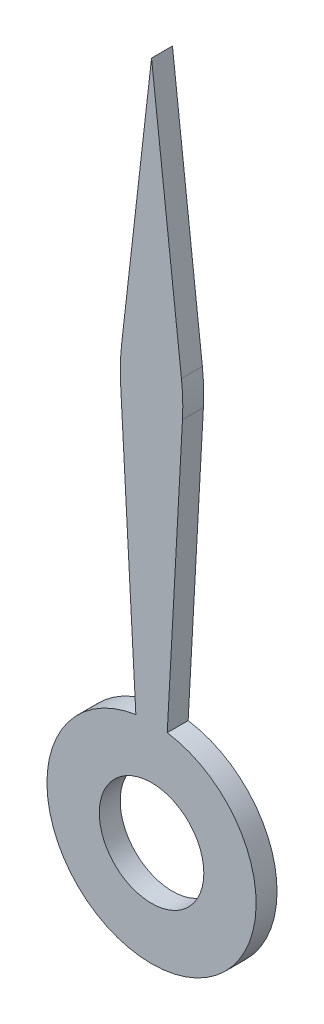
SolidWorks part; units mm, degrees
ref_plane "Front Plane" through (0, 0, 0) normal (0, 0, 1) x (1, 0, 0)
ref_plane "Top Plane" through (0, 0, 0) normal (0, 1, 0) x (1, 0, 0)
ref_plane "Right Plane" through (0, 0, 0) normal (1, 0, 0) x (0, 0, -1)
sketch "Sketch1" plane through (0, 0, 0) normal (0, 0, 1) x (1, 0, 0)
  line L0 (0, 0) -> (0, 6.5) construction
  line L1 (0, 6.5) -> (-0.286, 3.9895)
  line L2 (-0.2959, 3.6538) -> (-0.15, 0.9887)
  line L3 (0.2959, 3.6538) -> (0.15, 0.9887)
  line L4 (0, 6.5) -> (0.286, 3.9895)
  circle A0 centre (0, 0) radius 0.5
  arc A1 (-0.15, 0.9887) -> (0.15, 0.9887) centre (0, 0) ccw
  arc A2 (-0.286, 3.9895) -> (-0.2959, 3.6538) centre (1.7011, 3.7631) ccw
  arc A3 (0.286, 3.9895) -> (0.2959, 3.6538) centre (-1.7011, 3.7631) cw
  dimension "D1" = 1
  dimension "D2" = 2
  dimension "D4" = 2
  dimension "D3" = 6.5
  dimension "D5" = 0.3
extrude "Boss-Extrude1" add sketch "Sketch1" along normal blind 0.2
